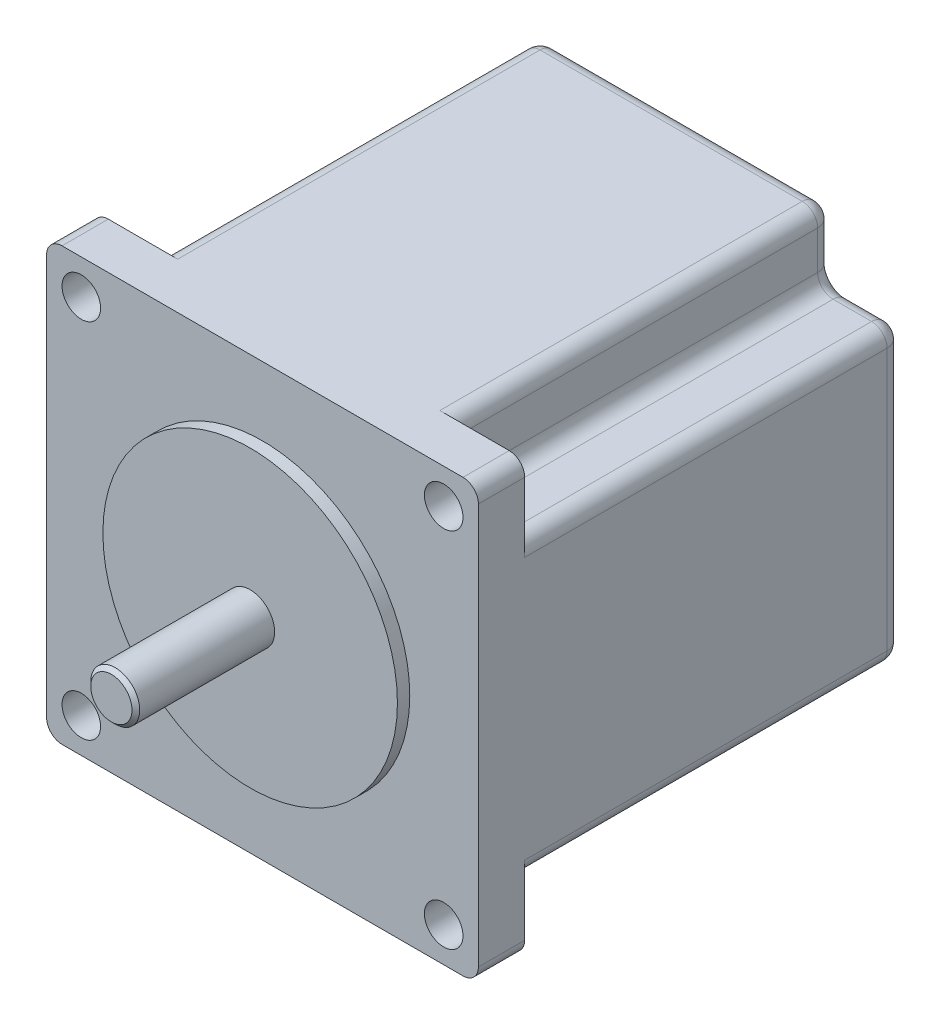
SolidWorks part; units mm, degrees
ref_plane "Спереди" through (0, 0, 0) normal (0, 0, 1) x (1, 0, 0)
ref_plane "Сверху" through (0, 0, 0) normal (0, 1, 0) x (1, 0, 0)
ref_plane "Справа" through (0, 0, 0) normal (1, 0, 0) x (0, 0, -1)
sketch "Эскиз1" plane through (0, 0, 0) normal (0, 0, 1) x (1, 0, 0)
  line L1 (0, 0) -> (56, 0)
  line L2 (0, 0) -> (0, 56)
  line L3 (0, 56) -> (56, 56)
  line L4 (56, 0) -> (56, 56)
  dimension "D1" = 56
  dimension "D2" = 56
extrude "Вытянуть1" add sketch "Эскиз1" along normal blind 55
sketch "Эскиз2" plane through (0, 0, 0) normal (0, 0, -1) x (-1, 0, 0)
  line L1 (-56, 56) -> (-47, 56)
  line L2 (-56, 56) -> (-56, 47)
  line L3 (-56, 47) -> (-47, 47)
  line L4 (-47, 56) -> (-47, 47)
  line L6 (0, 56) -> (0, 47)
  line L7 (0, 56) -> (-9, 56)
  line L8 (-9, 56) -> (-9, 47)
  line L9 (0, 47) -> (-9, 47)
  line L10 (0, 0) -> (-9, 0)
  line L11 (0, 0) -> (0, 9)
  line L12 (0, 9) -> (-9, 9)
  line L13 (-9, 0) -> (-9, 9)
  line L14 (-56, 0) -> (-56, 9)
  line L15 (-56, 0) -> (-47, 0)
  line L16 (-47, 0) -> (-47, 9)
  line L17 (-56, 9) -> (-47, 9)
  dimension "D1" = 9
  dimension "D2" = 9
extrude "Вырез-Вытянуть1" cut sketch "Эскиз2" against normal blind 49
fillet "Скругление1" radius 2 28 edges at (56, 28, 0) (51.5, 47, 0) (47, 51.5, 0) (28, 56, 0) (9, 51.5, 0) (4.5, 47, 0) (0, 28, 0) (4.5, 9, 0) (9, 4.5, 0) (28, 0, 0) (47, 4.5, 0) (51.5, 9, 0) (56, 56, 52) (0, 56, 52) (0, 0, 52) (56, 0, 52) (47, 0, 24.5) (47, 9, 24.5) (56, 9, 24.5) (9, 0, 24.5) (9, 9, 24.5) (0, 9, 24.5) (0, 47, 24.5) (9, 47, 24.5) (9, 56, 24.5) (47, 56, 24.5) (47, 47, 24.5) (56, 47, 24.5)
sketch "Эскиз3" plane through (0, 0, 55) normal (0, 0, 1) x (1, 0, 0)
  line L0 (0.5858, 55.4142) -> (55.4142, 0.5858) construction
  arc A0 (2, 56) -> (0, 54) centre (2, 54) ccw construction
  arc A1 (54, 0) -> (56, 2) centre (54, 2) ccw construction
  circle A2 centre (28, 28) radius 19.1
extrude "Вытянуть2" add sketch "Эскиз3" along normal blind 1.6
sketch "Эскиз4" plane through (0, 0, 56.6) normal (0, 0, 1) x (1, 0, 0)
  circle A0 centre (28, 28) radius 3.175
extrude "Вытянуть3" add sketch "Эскиз4" along normal blind 18
sketch "Эскиз5" plane through (0, 0, 55) normal (0, 0, 1) x (1, 0, 0)
  line L0 (4.5, 51.5) -> (51.5, 51.5) construction
  line L1 (4.5, 51.5) -> (4.5, 4.5) construction
  circle A0 centre (4.5, 51.5) radius 2.5
  circle A1 centre (28, 28) radius 19.1 construction
  circle A2 centre (28, 28) radius 19.1 construction
  circle A3 centre (51.5, 51.5) radius 2.5
  circle A4 centre (4.5, 4.5) radius 2.5
  circle A5 centre (51.5, 4.5) radius 2.5
  dimension "D1" = 23.5
  dimension "D2" = 23.5
  dimension "D3" = 5
  dimension "D4" = 90
extrude "Вырез-Вытянуть2" cut sketch "Эскиз5" against normal blind 18
chamfer "Фаска1" distance 0.5 angle 45 1 edges at (31.175, 28, 74.6)
